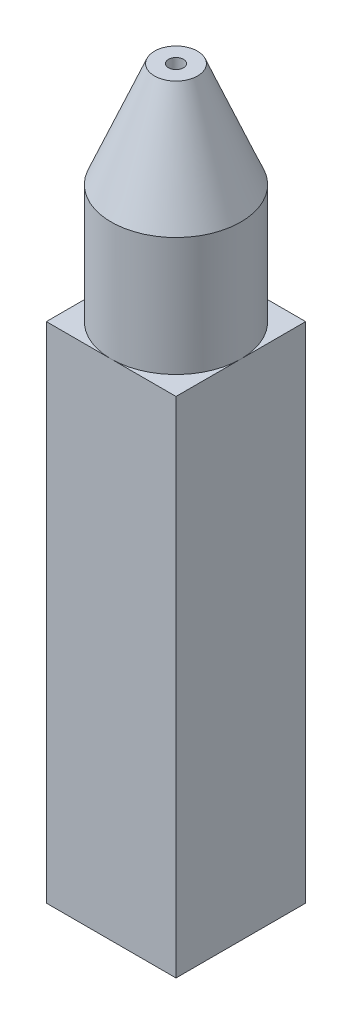
SolidWorks part; units mm, degrees
material "Brass"
ref_plane "Front Plane" through (0, 0, 0) normal (0, 0, 1) x (1, 0, 0)
ref_plane "Top Plane" through (0, 0, 0) normal (0, 1, 0) x (1, 0, 0)
ref_plane "Right Plane" through (0, 0, 0) normal (1, 0, 0) x (0, 0, -1)
sketch "Sketch1" plane through (0, 0, 0) normal (0, 0, 1) x (1, 0, 0)
  line L0 (0, 0) -> (0, 33.4708) construction
  line L5 (-0.3429, 9.3155) -> (-0.9906, 8.1936)
  line L6 (-0.9906, 8.1936) -> (-0.9906, 0)
  line L7 (-0.3429, 33.4708) -> (-0.9906, 33.4708)
  line L8 (-0.9906, 33.4708) -> (-2.9845, 28.6448)
  line L9 (-2.9845, 28.6448) -> (-2.9845, 0)
  line L10 (-0.3429, 33.4708) -> (-0.3429, 9.3155)
  line L11 (0, 33.4708) -> (-0.3429, 33.4708) construction
  line L12 (0, 0) -> (-0.9906, 0)
  line L13 (-0.9906, 0) -> (-2.9845, 0)
  point P3 (-1.4267, 0.496)
  point P4 (-0.3429, 1.3857)
  point P12 (0, 2.5544)
  point P13 (-0.9645, 1.2362)
  dimension "D1" = 0.3429
  dimension "D2" = 0.9906
  dimension "D3" = 4.826
  dimension "D4" = 2.9845
  dimension "D5" = 33.4708
  dimension "D6" = 24.1554
  dimension "D7" = 0.9906
  dimension "D8" = 30
revolve "Revolve1" add sketch "Sketch1" angle 360 about L0
sketch "Sketch2" plane through (0, 0, 0) normal (0, -1, 0) x (1, 0, 0)
  line L1 (-2.9845, 2.9845) -> (2.9845, 2.9845)
  line L2 (-2.9845, 2.9845) -> (-2.9845, -2.9845)
  line L3 (-2.9845, -2.9845) -> (2.9845, -2.9845)
  line L4 (2.9845, 2.9845) -> (2.9845, -2.9845)
  line L5 (-2.9845, 2.9845) -> (2.9845, -2.9845) construction
  line L6 (-2.9845, -2.9845) -> (2.9845, 2.9845) construction
  circle A0 centre (0, 0) radius 2.9845 construction
  circle A1 centre (0, 0) radius 2.9845
  point P0 (0, 0)
  circle M5 centre (0, 0) radius 2.9845
ref_plane "Plane1" through (0, 23.1838, 0) normal (0, 1, 0) x (1, 0, 0)
extrude "Boss-Extrude2" add sketch "Sketch2" against normal up to surface (23.1838 mm away) contours L4 L1 M5 | L1 L2 M5 | L4 L3 M5 | L2 L3 M5 up to plane "Plane1"
